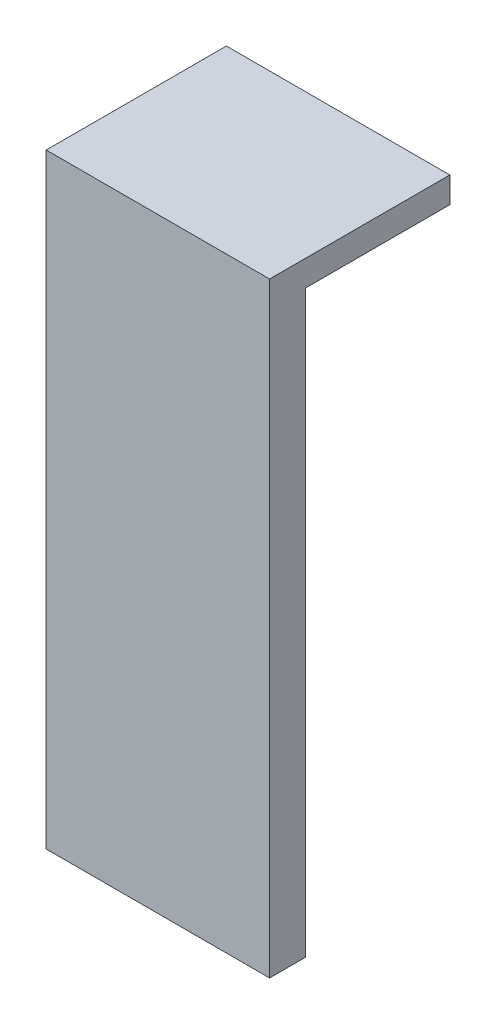
SolidWorks part; units mm, degrees
ref_plane "Front Plane" through (0, 0, 0) normal (0, 0, 1) x (1, 0, 0)
ref_plane "Top Plane" through (0, 0, 0) normal (0, 1, 0) x (1, 0, 0)
ref_plane "Right Plane" through (0, 0, 0) normal (1, 0, 0) x (0, 0, -1)
sketch "Sketch1" plane through (0, 0, 0) normal (0, 1, 0) x (1, 0, 0)
  line L1 (-4.2545, 1.27) -> (3.6195, 1.27)
  line L2 (-4.2545, 1.27) -> (-4.2545, 0)
  line L3 (-4.2545, 0) -> (3.6195, 0)
  line L4 (3.6195, 1.27) -> (3.6195, 0)
  point P4 (3.6195, 0.635)
  dimension "D1" = 7.874
  dimension "D2" = 1.27
extrude "Boss-Extrude1" add sketch "Sketch1" along normal blind 21.336
sketch "Sketch2" plane through (0, 0, -1.27) normal (0, 0, -1) x (-1, 0, 0)
  line L0 (-3.6195, 21.336) -> (-3.6195, 0) construction
  line L1 (-3.6195, 21.336) -> (4.2545, 21.336)
  line L2 (-3.6195, 21.336) -> (-3.6195, 20.4278)
  line L3 (-3.6195, 20.4278) -> (4.2545, 20.4278)
  line L4 (4.2545, 21.336) -> (4.2545, 20.4278)
  line L5 (4.2545, 21.336) -> (4.2545, 0) construction
extrude "Boss-Extrude2" add sketch "Sketch2" along normal blind 5.08
